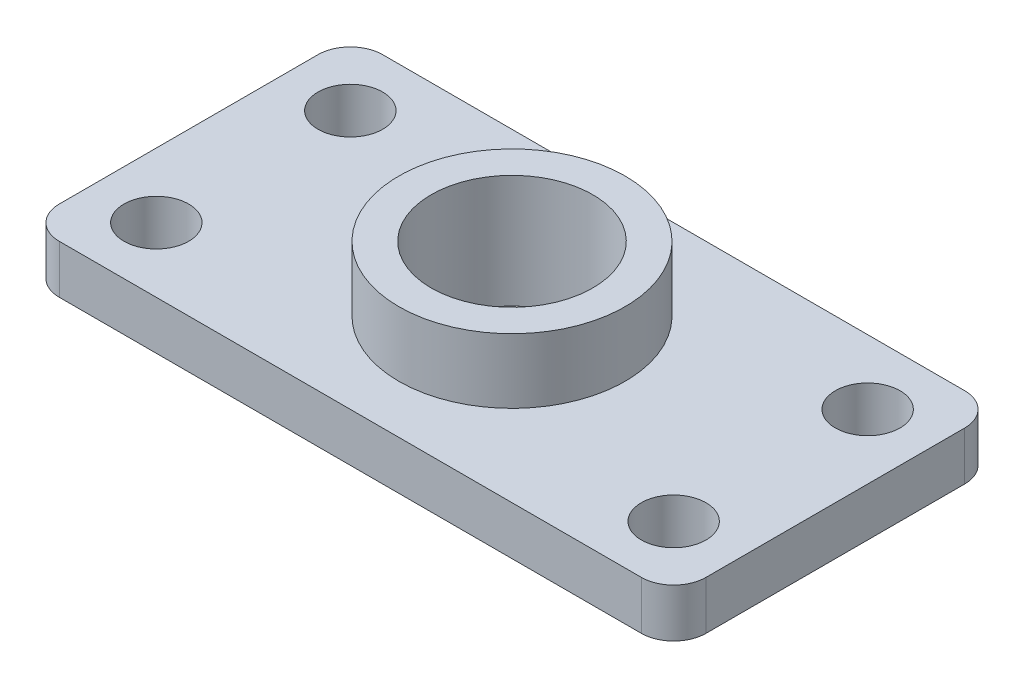
SolidWorks part; units mm, degrees
ref_plane "Спереди" through (0, 0, 0) normal (0, 0, 1) x (1, 0, 0)
ref_plane "Сверху" through (0, 0, 0) normal (0, 1, 0) x (1, 0, 0)
ref_plane "Справа" through (0, 0, 0) normal (1, 0, 0) x (0, 0, -1)
sketch "Эскиз1" plane through (0, 0, 0) normal (0, 1, 0) x (1, 0, 0)
  line L1 (0, 0) -> (200, 0)
  line L2 (0, 0) -> (0, 100)
  line L3 (0, 100) -> (200, 100)
  line L4 (200, 0) -> (200, 100)
  point P5 (0, 0)
  dimension "D1" = 100
  dimension "D2" = 200
extrude "Бобышка-Вытянуть1" add sketch "Эскиз1" along normal blind 15 contours L2 L3 L4 L1
sketch "Эскиз2" plane through (0, 15, 0) normal (0, 1, 0) x (1, 0, 0)
  circle A0 centre (100, 50) radius 35
  point P6 (96.9889, 51.2739)
  point P10 (51.8231, 0)
  point P13 (82.4326, 61.8452)
  point P14 (0, 0)
  dimension "D1" = 70
  dimension "D2" = 50
  dimension "D3" = 100
extrude "Бобышка-Вытянуть2" add sketch "Эскиз2" along normal blind 20
sketch "Эскиз3" plane through (0, 35, 0) normal (0, 1, 0) x (1, 0, 0)
  circle A0 centre (100, 50) radius 25
  dimension "D1" = 50
extrude "Вырез-Вытянуть1" cut sketch "Эскиз3" against normal through all
sketch "Эскиз4" plane through (0, 15, 0) normal (0, 1, 0) x (1, 0, 0)
  circle A0 centre (20, 20) radius 10
  circle A1 centre (20, 80) radius 10
  circle A2 centre (180, 80) radius 10
  circle A3 centre (180, 20) radius 10
  point P8 (0, 0)
  dimension "D1" = 20
  dimension "D2" = 20
  dimension "D3" = 20
  dimension "D4" = 20
  dimension "D5" = 20
  dimension "D6" = 20
  dimension "D7" = 20
extrude "Вырез-Вытянуть2" cut sketch "Эскиз4" against normal through all
fillet "Скругление1" radius 10 4 edges at (200, 7.5, -100) (200, 7.5, 0) (0, 7.5, -100) (0, 7.5, 0)
